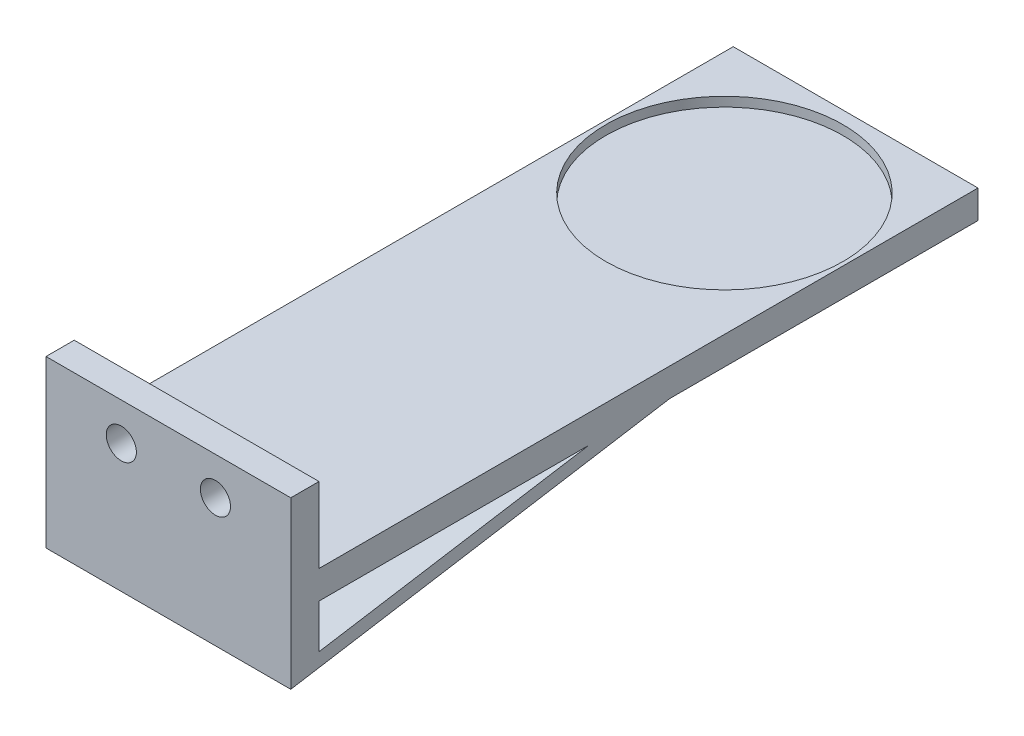
SolidWorks part; units mm, degrees
ref_plane "前视基准面" through (0, 0, 0) normal (0, 0, 1) x (1, 0, 0)
ref_plane "上视基准面" through (0, 0, 0) normal (0, 1, 0) x (1, 0, 0)
ref_plane "右视基准面" through (0, 0, 0) normal (1, 0, 0) x (0, 0, -1)
sketch "草图1" plane through (0, 0, 0) normal (1, 0, 0) x (0, 0, -1)
  line L0 (-36.5, -8.1192) -> (3.7552, -1.5)
  line L1 (-36.5, -1.5) -> (36.5, -1.5)
  line L2 (-36.5, -1.5) -> (-36.5, 1.5)
  line L3 (-36.5, 1.5) -> (36.5, 1.5)
  line L4 (36.5, -1.5) -> (36.5, 1.5)
  line L5 (-36.5, -1.5) -> (36.5, 1.5) construction
  line L6 (-36.5, 1.5) -> (36.5, -1.5) construction
  line L7 (-36.5, 1.5) -> (-33.5, 1.5)
  line L8 (-36.5, 1.5) -> (-36.5, 9.5)
  line L9 (-36.5, 9.5) -> (-33.5, 9.5)
  line L10 (-33.5, 1.5) -> (-33.5, 9.5)
  line L11 (-36.5, -1.5) -> (3.7552, -1.5)
  line L12 (-36.5, -1.5) -> (-36.5, -8.1192)
  line L13 (-36.5, -8.1192) -> (3.7552, -8.1192)
  line L14 (3.7552, -1.5) -> (3.7552, -8.1192)
  line L15 (-33.5, -6.1604) -> (-4.8611, -1.5)
  line L16 (-33.5, 1.5) -> (-4.8611, 1.5)
  line L17 (-33.5, 1.5) -> (-33.5, -6.1604)
  line L18 (-33.5, -6.1604) -> (-4.8611, -6.1604)
  line L19 (-4.8611, 1.5) -> (-4.8611, -6.1604)
  point P0 (0, 0)
  dimension "D1" = 73
  dimension "D2" = 3
  dimension "D3" = 3
  dimension "D4" = 8
extrude "凸台-拉伸1" add sketch "草图1" along normal blind 26 contours L3 L10 L9 L8 | L1 L4 L3 L2 | L1 L12 L0 | L17 L3 L2 L1 | L19 L3 L17 L11 | L19 L15 L18 L0 | L11 L19 L0
sketch "草图2" plane through (0, 0, 36.5) normal (0, 0, 1) x (1, 0, 0)
  line L0 (26, 9.5) -> (0, 9.5) construction
  line L1 (0, -8.1192) -> (0, 9.5) construction
  circle A0 centre (8, 5.5) radius 1.6
  circle A1 centre (18, 5.5) radius 1.6
  dimension "D1" = 4
  dimension "D2" = 4
  dimension "D3" = 8
  dimension "D4" = 10
extrude "切除-拉伸1" cut sketch "草图2" against normal blind 10
sketch "草图3" plane through (0, 1.5, 0) normal (0, 1, 0) x (1, 0, 0)
  line L0 (0, -33.5) -> (0, 36.5) construction
  circle A0 centre (13, 22.5632) radius 12.6
  dimension "D1" = 13
extrude "切除-拉伸2" cut sketch "草图3" against normal blind 1
